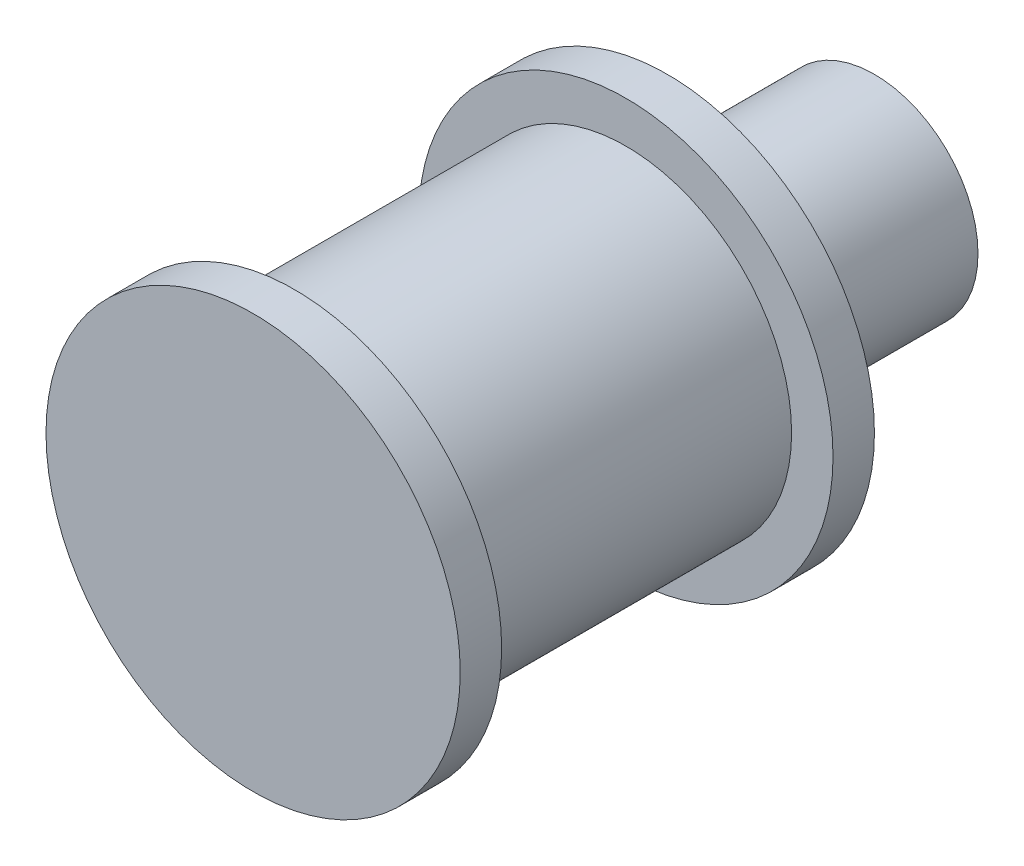
SolidWorks part; units mm, degrees
ref_plane "Front Plane" through (0, 0, 0) normal (0, 0, 1) x (1, 0, 0)
ref_plane "Top Plane" through (0, 0, 0) normal (0, 1, 0) x (1, 0, 0)
ref_plane "Right Plane" through (0, 0, 0) normal (1, 0, 0) x (0, 0, -1)
sketch "Sketch1" plane through (0, 0, 0) normal (0, 0, 1) x (1, 0, 0)
  circle A0 centre (0, 0) radius 2.5
  dimension "D1" = 5
extrude "Boss-Extrude1" add sketch "Sketch1" along normal blind 5
sketch "Sketch2" plane through (0, 0, 5) normal (0, 0, 1) x (1, 0, 0)
  circle A0 centre (0, 0) radius 5
  dimension "D1" = 10
extrude "Boss-Extrude2" add sketch "Sketch2" along normal blind 1
sketch "Sketch3" plane through (0, 0, 6) normal (0, 0, 1) x (1, 0, 0)
  circle A0 centre (0, 0) radius 4
  dimension "D1" = 8
extrude "Boss-Extrude3" add sketch "Sketch3" along normal blind 8
sketch "Sketch4" plane through (0, 0, 14) normal (0, 0, 1) x (1, 0, 0)
  circle A0 centre (0, 0) radius 5
  dimension "D1" = 10
extrude "Boss-Extrude4" add sketch "Sketch4" along normal blind 1
